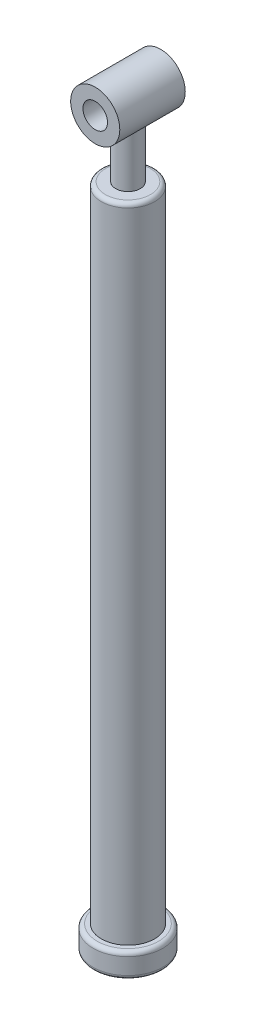
SolidWorks part; units mm, degrees
ref_plane "Front Plane" through (0, 0, 0) normal (0, 0, 1) x (1, 0, 0)
ref_plane "Top Plane" through (0, 0, 0) normal (0, 1, 0) x (1, 0, 0)
ref_plane "Right Plane" through (0, 0, 0) normal (1, 0, 0) x (0, 0, -1)
sketch "Sketch1" plane through (0, 0, 0) normal (0, 0, 1) x (1, 0, 0)
  line L0 (0, 143.9048) -> (0, -147.4147) construction
  line L1 (-19.9999, -125.5578) -> (-37.5, -125.5578)
  line L2 (-42.5, -120.5578) -> (-42.5, -100.5578)
  line L3 (-37.5, -95.5578) -> (-32.5, -95.5578)
  line L4 (-32.5, -95.5578) -> (-32.5, 684.4422)
  line L5 (-27.5001, 689.4421) -> (-15, 689.4421)
  line L6 (-15, 689.4421) -> (-15, -120.5579)
  arc A0 (-42.5, -100.5578) -> (-37.5, -95.5578) centre (-37.5, -100.5578) cw
  arc A1 (-42.5, -120.5578) -> (-37.5, -125.5578) centre (-37.5, -120.5578) ccw
  arc A2 (-19.9999, -125.5578) -> (-15, -120.5579) centre (-19.9999, -120.5579) ccw
  arc A3 (-32.5, 684.4422) -> (-27.5001, 689.4421) centre (-27.5001, 684.4422) cw
  point P5 (-42.5, -110.5578)
  dimension "D5" = 5
  dimension "D6" = 5
  dimension "D7" = 4.9999
  dimension "D8" = 4.9999
  dimension "D1" = 30
  dimension "D2" = 15
  dimension "D3" = 42.5
  dimension "D4" = 32.5
  dimension "D9" = 780
  dimension "D10" = 19.9999
revolve "Revolve1" add sketch "Sketch1" angle 360 about L0
sketch "Sketch3" plane through (0, 0, 0) normal (0, 0, 1) x (1, 0, 0)
  circle A0 centre (0, 779.4421) radius 30
  circle A1 centre (0, 779.4421) radius 15
  dimension "D2" = 60
  dimension "D3" = 30
extrude "Boss-Extrude2" add sketch "Sketch3" along normal mid plane 80 separate body
sketch "Sketch4" plane through (0, 689.4421, 0) normal (0, 1, 0) x (1, 0, 0)
  circle A0 centre (0, 0) radius 15
  dimension "D1" = 30
extrude "Boss-Extrude3" add sketch "Sketch4" along normal up to next
